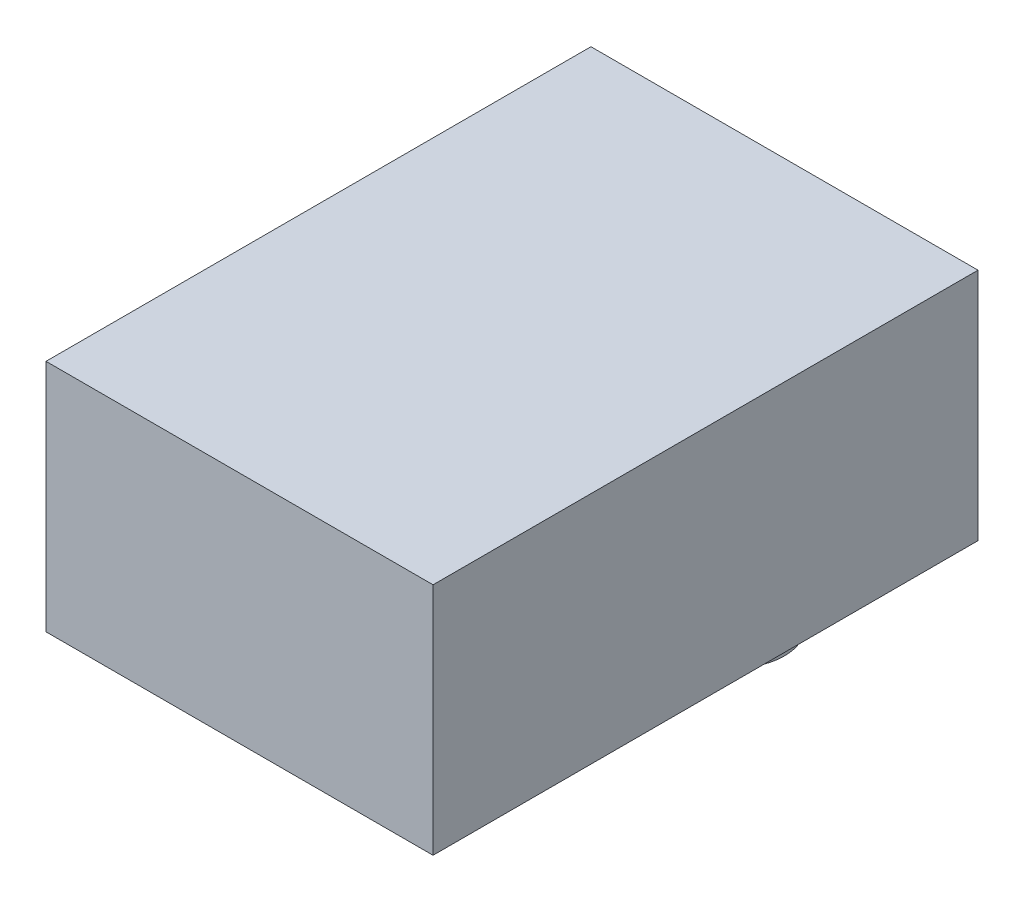
SolidWorks part; units mm, degrees
ref_plane "Front Plane" through (0, 0, 0) normal (0, 0, 1) x (1, 0, 0)
ref_plane "Top Plane" through (0, 0, 0) normal (0, 1, 0) x (1, 0, 0)
ref_plane "Right Plane" through (0, 0, 0) normal (1, 0, 0) x (0, 0, -1)
sketch "Sketch1" plane through (0, 0, 0) normal (0, 1, 0) x (1, 0, 0)
  line L0 (-0.5, 4.9749) -> (-0.5, 7)
  line L1 (-0.5, 7) -> (0.5, 7)
  line L2 (0.5, 7) -> (0.5, 4.9749)
  line L3 (-3.8714, 3.1643) -> (-5.2907, 4.5836)
  line L4 (-5.2907, 4.5836) -> (-4.5836, 5.2907)
  line L5 (-4.5836, 5.2907) -> (-3.1643, 3.8714)
  circle A0 centre (0, 0) radius 5
  circle A1 centre (0, 0) radius 2.35
  point P7 (0, 7)
  dimension "D1" = 1
  dimension "D3" = 10
  dimension "D7" = 4.7
  dimension "D2" = 1
  dimension "D4" = 7
  dimension "D5" = 45
  dimension "D6" = 7
extrude "Boss-Extrude1" add sketch "Sketch1" along normal blind 9.3 contours A0 | A0 L2 L1 L0 | A0 L5 L4 L3
sketch "Sketch2" plane through (0, 9.3, 0) normal (0, 1, 0) x (1, 0, 0)
  circle A0 centre (0, 0) radius 2.8
  dimension "D1" = 5.6
extrude "Cut-Extrude1" cut sketch "Sketch2" against normal offset from surface (6.5 mm away) 2.8 up to face at (0, 0, 2.35)
sketch "Sketch3" plane through (0, 9.3, 0) normal (0, 1, 0) x (1, 0, 0)
  line L1 (-24, 10) -> (14, 10)
  line L2 (-24, 10) -> (-24, -43.5)
  line L3 (-24, -43.5) -> (14, -43.5)
  line L4 (14, 10) -> (14, -43.5)
  dimension "D4" = 14
  dimension "D1" = 38
  dimension "D2" = 53.5
  dimension "D3" = 10
extrude "Boss-Extrude2" add sketch "Sketch3" along normal blind 23
